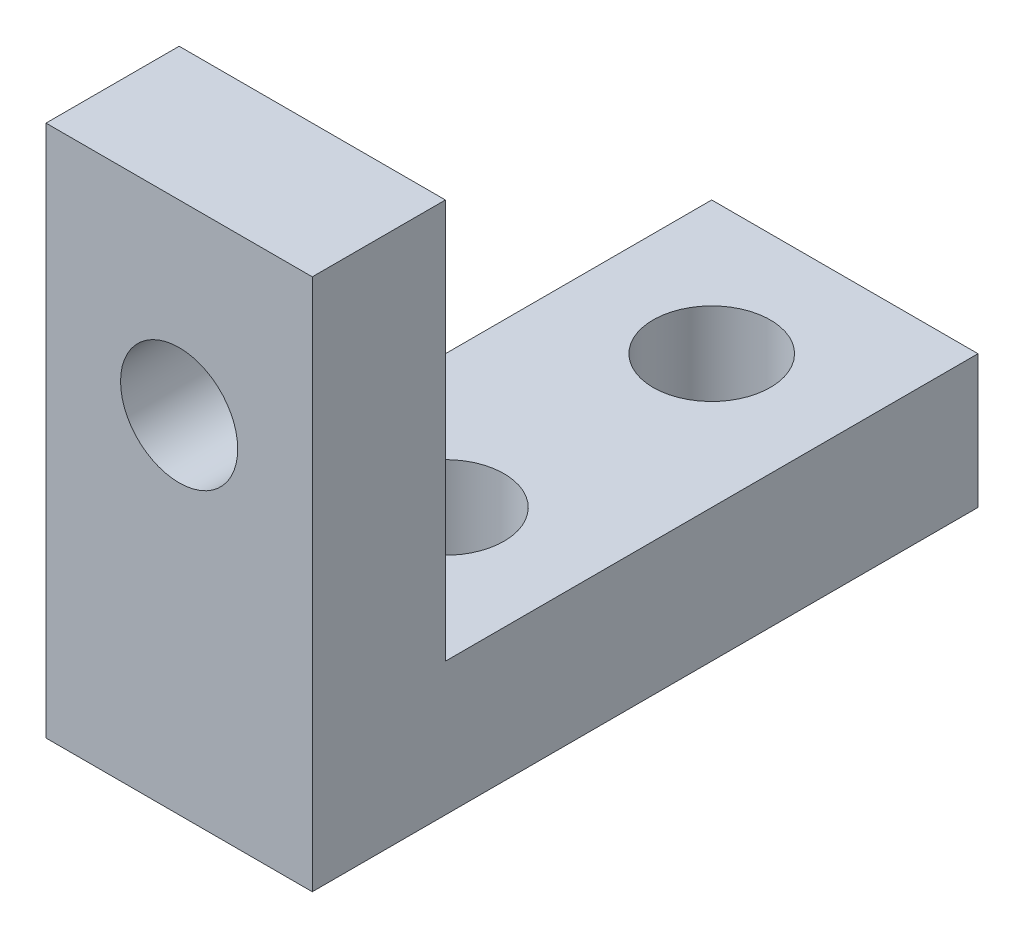
SolidWorks part; units mm, degrees
ref_plane "Front Plane" through (0, 0, 0) normal (0, 0, 1) x (1, 0, 0)
ref_plane "Top Plane" through (0, 0, 0) normal (0, 1, 0) x (1, 0, 0)
ref_plane "Right Plane" through (0, 0, 0) normal (1, 0, 0) x (0, 0, -1)
sketch "Sketch1" plane through (0, 0, 0) normal (1, 0, 0) x (0, 0, -1)
  line L1 (0, 0) -> (5, 0)
  line L2 (0, 0) -> (0, 20)
  line L3 (0, 20) -> (5, 20)
  line L4 (5, 0) -> (5, 20)
  line L5 (0, 0) -> (25, 0)
  line L6 (0, 0) -> (0, 5)
  line L7 (0, 5) -> (25, 5)
  line L8 (25, 0) -> (25, 5)
  dimension "D1" = 20
  dimension "D2" = 5
  dimension "D3" = 5
  dimension "D4" = 25
extrude "Boss-Extrude1" add sketch "Sketch1" along normal blind 10 contours L2 L7 L4 L3 | L7 L2 L1 L4 | L5 L8 L7 L4
sketch "Sketch2" plane through (0, 0, -5) normal (0, 0, -1) x (-1, 0, 0)
  line L0 (-5, 20) -> (-5, 5) construction
  line L1 (-10, 20) -> (0, 20) construction
  line L2 (-10, 5) -> (0, 5) construction
  circle A0 centre (-5, 13) radius 2.2
  dimension "D1" = 4.4
  dimension "D2" = 7
extrude "Cut-Extrude1" cut sketch "Sketch2" against normal blind 10
sketch "Sketch3" plane through (0, 5, 0) normal (0, 1, 0) x (1, 0, 0)
  line L0 (5, 5) -> (5, 25) construction
  line L1 (10, 5) -> (0, 5) construction
  line L2 (10, 25) -> (0, 25) construction
  circle A0 centre (5, 20) radius 2.2
  circle A1 centre (5, 10) radius 2.2
  dimension "D1" = 4.4
  dimension "D2" = 4.4
  dimension "D3" = 5
  dimension "D4" = 10
extrude "Cut-Extrude2" cut sketch "Sketch3" against normal blind 10
